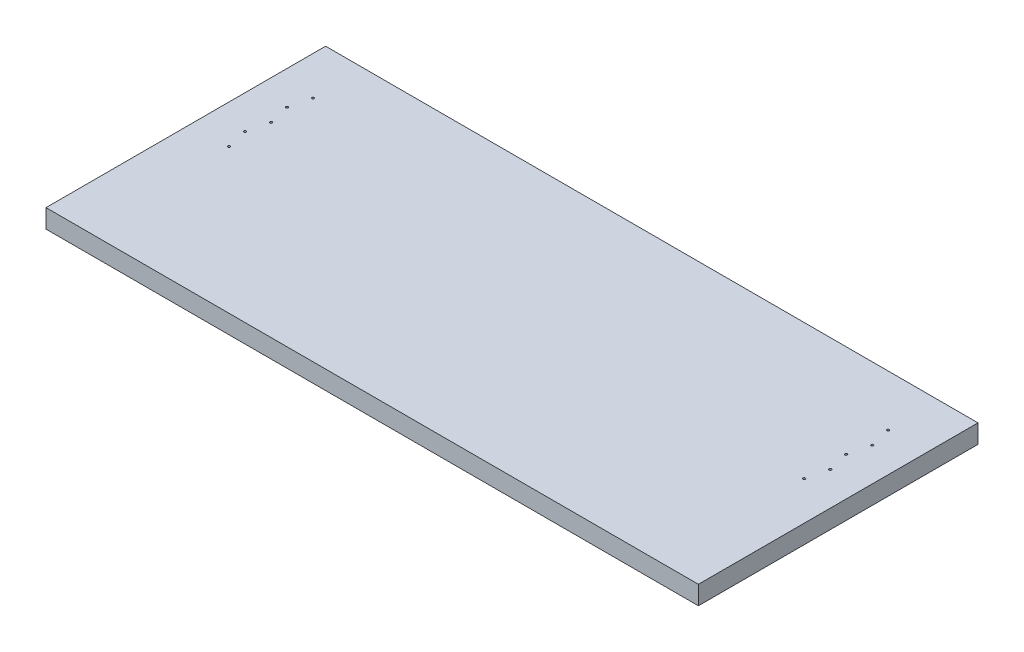
SolidWorks part; units mm, degrees
other "Markup1"
sketch "Sketch3" plane through (-700, 50, -300) normal (0, 1, 0) x (1, 0, 0)
ref_plane "Front Plane" through (0, 0, 0) normal (0, 0, 1) x (1, 0, 0)
ref_plane "Top Plane" through (0, 0, 0) normal (0, 1, 0) x (1, 0, 0)
ref_plane "Right Plane" through (0, 0, 0) normal (1, 0, 0) x (0, 0, -1)
sketch "Sketch1" plane through (0, 0, 0) normal (0, 1, 0) x (1, 0, 0)
  line L1 (-700, -300) -> (700, -300)
  line L2 (-700, -300) -> (-700, 300)
  line L3 (-700, 300) -> (700, 300)
  line L4 (700, -300) -> (700, 300)
  line L5 (-700, -300) -> (700, 300) construction
  line L6 (-700, 300) -> (700, -300) construction
  point P0 (0, 0)
  dimension "D1" = 1400
  dimension "D2" = 600
extrude "Boss-Extrude1" add sketch "Sketch1" along normal blind 40
sketch "Sketch2" plane through (0, 0, 0) normal (0, 1, 0) x (1, 0, 0)
  line L0 (700, 300) -> (-700, 300) construction
  line L3 (700, -300) -> (700, 300) construction
  circle A1 centre (617, 10) radius 2.5
  circle A2 centre (628, 55) radius 2.5
  circle A3 centre (617, 100) radius 2.5
  circle A4 centre (628, 145) radius 2.5
  circle A5 centre (617, 190) radius 2.5
  dimension "D1" = 5
  dimension "D2" = 5
  dimension "D3" = 45
  dimension "D4" = 45
  dimension "D5" = 45
  dimension "D6" = 200
  dimension "D8" = 45
  dimension "D7" = 72
  dimension "D9" = 11
extrude "Cut-Extrude9" cut sketch "Sketch2" along normal blind 70
ref_plane "Plane1" through (0, 0, 0) normal (-1, 0, 0) x (0, 0, 1)
mirror "Mirror1" about plane through (0, 0, 0) normal (-1, 0, 0) of "Cut-Extrude9"
